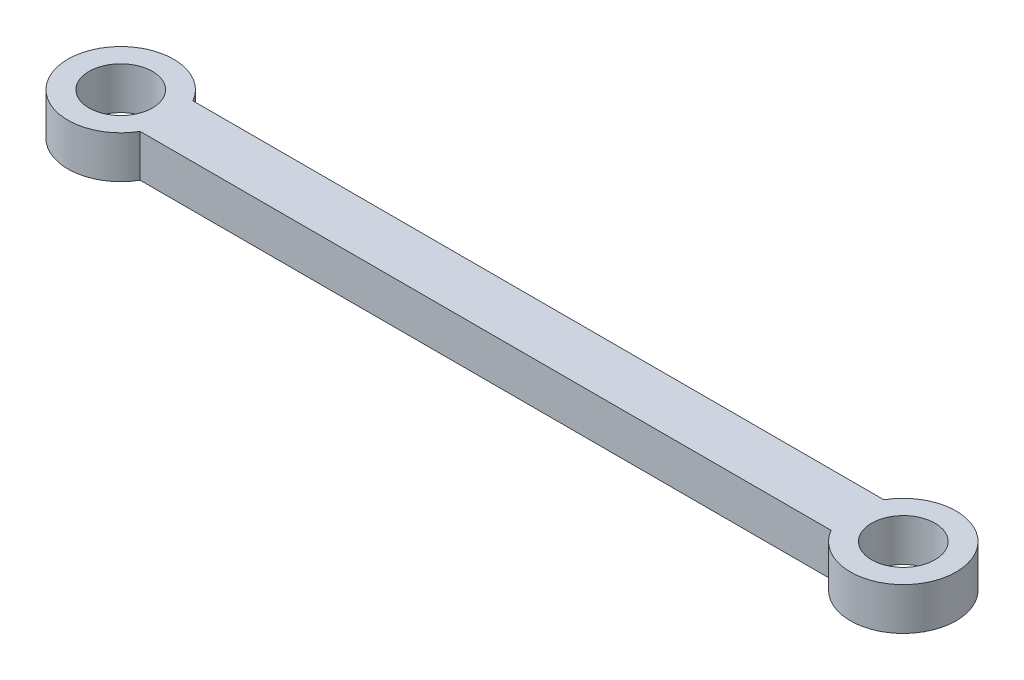
SolidWorks part; units mm, degrees
ref_plane "Front Plane" through (0, 0, 0) normal (0, 0, 1) x (1, 0, 0)
ref_plane "Top Plane" through (0, 0, 0) normal (0, 1, 0) x (1, 0, 0)
ref_plane "Right Plane" through (0, 0, 0) normal (1, 0, 0) x (0, 0, -1)
sketch "Sketch1" plane through (0, 0, 0) normal (0, 1, 0) x (1, 0, 0)
  line L0 (-9.6233, 9.6827) -> (23.0466, 9.6827)
  line L5 (-11.7883, 8.4327) -> (25.2117, 8.4327) construction
  line L6 (-9.6233, 7.1827) -> (23.0466, 7.1827)
  arc A6 (-9.6233, 9.6827) -> (-9.6233, 7.1827) centre (-11.7883, 8.4327) ccw
  arc A7 (23.0466, 7.1827) -> (23.0466, 9.6827) centre (25.2117, 8.4327) ccw
  circle A8 centre (25.2117, 8.4327) radius 1.5
  circle A9 centre (-11.7883, 8.4327) radius 1.5
  dimension "D3" = 3
  dimension "D4" = 1.25
  dimension "D2" = 5
  dimension "D1" = 37
extrude "Boss-Extrude2" add sketch "Sketch1" along normal blind 2
